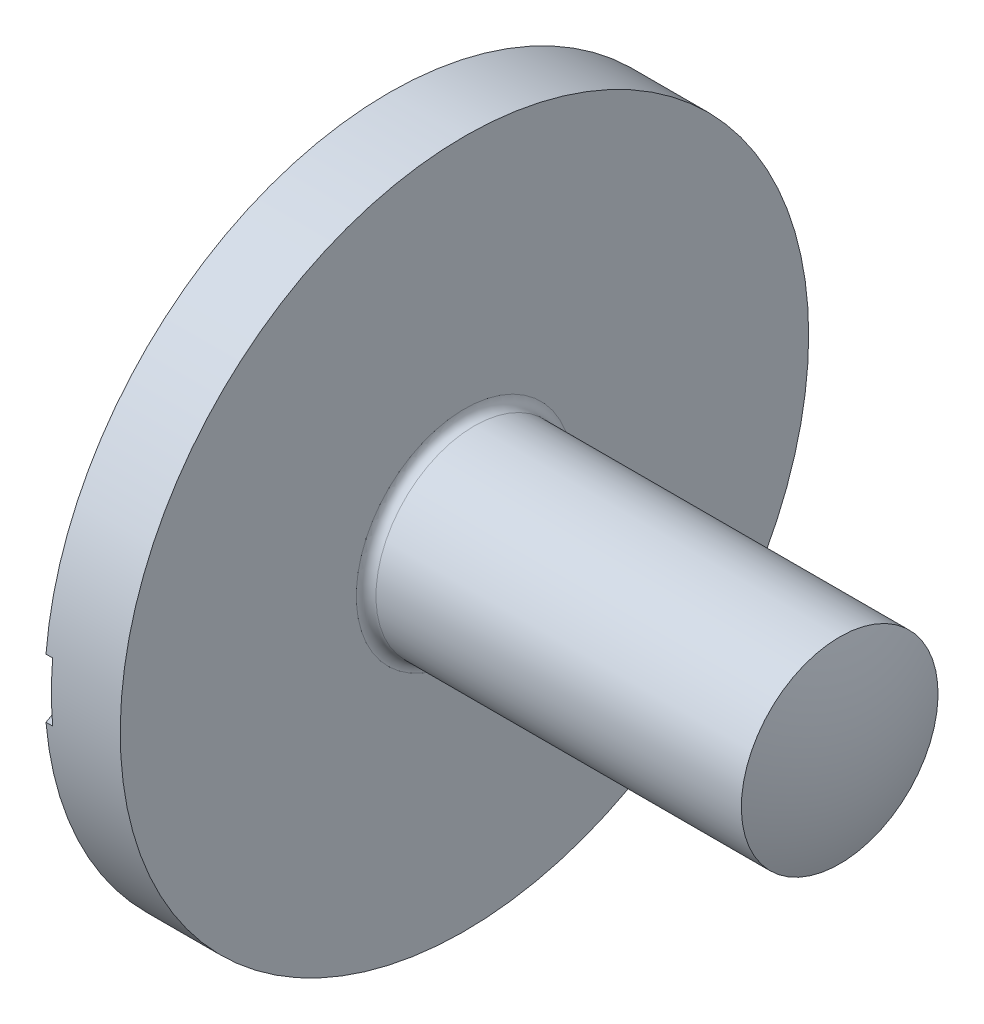
SolidWorks part; units mm, degrees
ref_plane "Front" through (0, 0, 0) normal (0, 0, 1) x (1, 0, 0)
ref_plane "Top" through (0, 0, 0) normal (0, 1, 0) x (1, 0, 0)
ref_plane "Right" through (0, 0, 0) normal (1, 0, 0) x (0, 0, -1)
sketch "Sketch1" plane through (0, 0, 0) normal (1, 0, 0) x (0, 0, -1)
  circle A0 centre (0, 0) radius 7
  dimension "dk" = 14
extrude "BaseHead" add sketch "Sketch1" along normal blind 2.8
sketch "Sketch2" plane through (2.8, 0.0676, 0.3015) normal (1, 0, 0) x (0, 0, -1)
  line L0 (0.3015, -0.0676) -> (1.3015, -0.0676) construction
  circle A0 centre (0.3015, -0.0676) radius 2
  circle A1 centre (0.3015, -0.0676) radius 7 construction
  dimension "d" = 4
  dimension "a" = 1
extrude "BaseBody" add sketch "Sketch2" along normal blind 8
cosmetic thread "ThreadCosmetic1" [suppressed] parameters "D1"=7, "D2"=3.242
sketch "Sketch3" plane through (0, 0, 0) normal (0, 0, 1) x (1, 0, 0)
  line L1 (0, 0.6) -> (1.4, 0.6)
  line L2 (0, 0.6) -> (0, -0.6)
  line L3 (0, -0.6) -> (1.4, -0.6)
  line L4 (1.4, 0.6) -> (1.4, -0.6)
  line L5 (0, 7) -> (0, -7) construction
  dimension "t" = 1.4
  dimension "n" = 1.2
  dimension "m" = 0.6
extrude "Slot" cut sketch "Sketch3" against normal through all and the other way through all
sketch "Sketch4" plane through (-5.7638, 3.9138, 0) normal (0, 0, 1) x (0, -1, 0)
  line L0 (3.9138, 15.0989) -> (3.9138, -3.5713) construction
  line L1 (1.9138, 16.5638) -> (1.9138, 8.5638) construction
  line L2 (-3.0862, 8.5638) -> (-3.0862, 5.7638) construction
  line L4 (1.9138, 18.5638) -> (1.9138, 16.1944)
  line L5 (3.9138, 16.5638) -> (3.9138, 18.5638)
  line L6 (3.9138, 18.5638) -> (1.9138, 18.5638)
  line L8 (-3.0862, 3.7638) -> (3.9138, 3.7638)
  line L9 (3.9138, 3.7638) -> (3.9138, 5.7638)
  line L10 (-3.0862, 7.0288) -> (-3.0862, 3.7638)
  line L11 (-3.0862, 5.7638) -> (3.3138, 5.7638) construction
  line L13 (5.9138, 16.5638) -> (1.9138, 16.5638) construction
  arc A0 (-3.0862, 7.0288) -> (3.9138, 5.7638) centre (3.9138, 25.7638) ccw
  arc A1 (3.9138, 16.5638) -> (1.9138, 16.1944) centre (3.9138, 10.9638) ccw
  dimension "re" = 5.6
  dimension "D2" = 2
  dimension "D3" = 2
  dimension "dr" = 20
revolve "BaseTop" cut sketch "Sketch4" angle 360 about L0
fillet "HeadFillet" radius 0.2 1 edges at (2.8, 0, -2)
sketch "Sketch5" plane through (0, 0, 0) normal (0, 0, 1) x (1, 0, 0)
  line L0 (10.4307, 1.6718) -> (10.6202, 2)
  line L1 (10.6202, 2) -> (10.6202, 2.379)
  line L2 (10.6202, 2.379) -> (10.2412, 2.379)
  line L3 (10.2412, 2.379) -> (10.2412, 2)
  line L4 (10.2412, 2) -> (10.4307, 1.6718)
  line L5 (10.4307, 2) -> (10.4307, -2) construction
  line L6 (0, 0) -> (7.0548, 0) construction
  dimension "D1" = 4
  dimension "D2" = 0.379
revolve "Cut-Revolve10" [suppressed] cut sketch "Sketch5" angle 360 about L6
pattern_linear "LPattern10" [suppressed] count 15 spacing 0.4548 along (1, 0, 0)
equation "\"m@Sketch3\" =\"n@Sketch3\" / 2"
equation "\"D1@ThreadCosmetic1\" = \"l@BaseBody\" -\"a@Sketch2\""
equation "\"D1@Sketch5\" = \"d@Sketch2\""
equation "\"D2@Sketch5\" =  ( \"d@Sketch2\" - \"D2@ThreadCosmetic1\" )  / 2"
equation "\"D3@LPattern10\" = \"D2@Sketch5\" * 1.2"
equation "\"D1@LPattern10\" = \"D1@ThreadCosmetic1\" / \"D3@LPattern10\""
